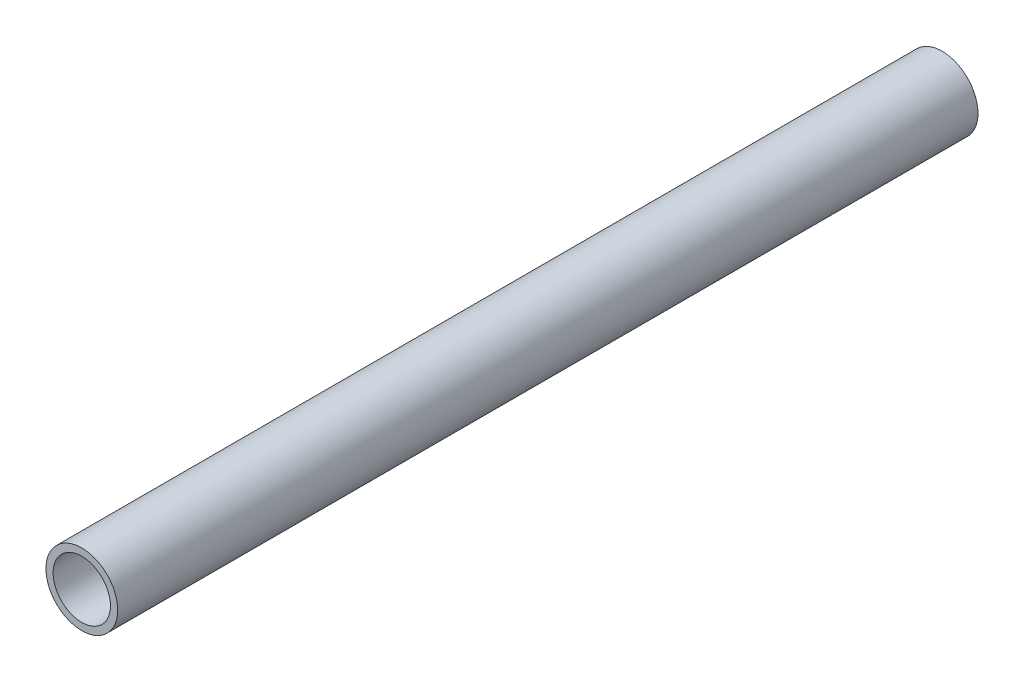
SolidWorks part; units mm, degrees
ref_plane "Front" through (0, 0, 0) normal (0, 0, 1) x (1, 0, 0)
ref_plane "Top" through (0, 0, 0) normal (0, 1, 0) x (1, 0, 0)
ref_plane "Right" through (0, 0, 0) normal (1, 0, 0) x (0, 0, -1)
sketch "草图2" plane through (0, 0, 0) normal (0, 0, 1) x (1, 0, 0)
  circle A0 centre (0, 0) radius 25
extrude "凸台-拉伸1" add sketch "草图2" along normal blind 600
sketch "草图3" plane through (0, 0, 600) normal (0, 0, 1) x (1, 0, 0)
  circle A0 centre (0, 0) radius 20
extrude "切除-拉伸1" cut sketch "草图3" against normal blind 600
